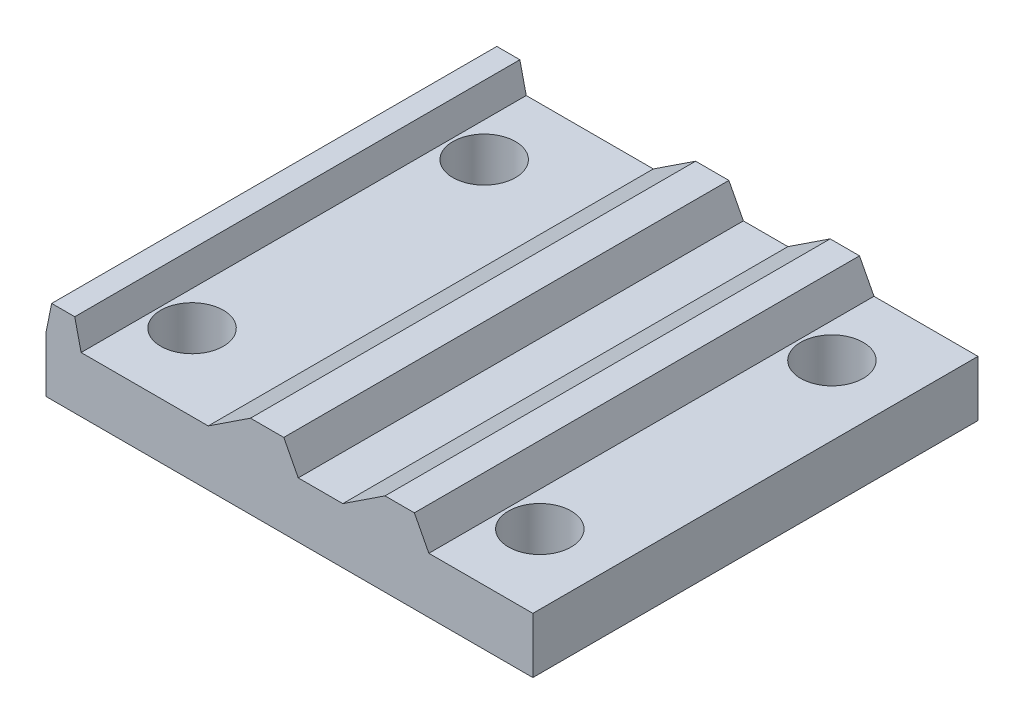
SolidWorks part; units mm, degrees
ref_plane "前视基准面" through (0, 0, 0) normal (0, 0, 1) x (1, 0, 0)
ref_plane "上视基准面" through (0, 0, 0) normal (0, 1, 0) x (1, 0, 0)
ref_plane "右视基准面" through (0, 0, 0) normal (1, 0, 0) x (0, 0, -1)
other "Configuration Table"
sketch "草图1" plane through (0, 0, 0) normal (0, 1, 0) x (1, 0, 0)
  line L0 (0, 0) -> (-4.3145, 0) construction
  line L1 (-17.5, -16) -> (17.5, -16)
  line L2 (-17.5, -16) -> (-17.5, 16)
  line L3 (-17.5, 16) -> (17.5, 16)
  line L4 (17.5, -16) -> (17.5, 16)
  line L5 (-17.5, -16) -> (17.5, 16) construction
  line L6 (-17.5, 16) -> (17.5, -16) construction
  line L7 (0, 0) -> (0, 5.4715) construction
  circle A0 centre (-12.5, 10.5) radius 2.25
  circle A1 centre (-12.5, -10.5) radius 2.25
  circle A2 centre (12.5, -10.5) radius 2.25
  circle A3 centre (12.5, 10.5) radius 2.25
  point P0 (0, 0)
  dimension "D3" = 4.5
  dimension "D1" = 35
  dimension "D2" = 32
  dimension "D4" = 21
  dimension "D5" = 25
extrude "凸台-拉伸1" add sketch "草图1" along normal blind 4
sketch "草图3" plane through (0, 0, 16) normal (0, 0, 1) x (1, 0, 0)
  line L0 (-17.5, 4) -> (-17.0918, 6)
  line L1 (-17.0918, 6) -> (-15.4333, 6)
  line L2 (-15.4333, 6) -> (-14.9752, 4)
  line L3 (-17.5, 4) -> (17.5, 4) construction
  line L4 (-14.9752, 4) -> (-10.8778, 4)
  line L8 (-8.0295, 4) -> (-5.8372, 4)
  line L9 (-5.8372, 4) -> (-2.8009, 6)
  line L10 (-2.8009, 6) -> (-0.4071, 6)
  line L11 (-0.4071, 6) -> (0.6341, 4)
  line L12 (0.6341, 4) -> (-5.8372, 4)
  line L13 (-8.0295, 4) -> (-10.8778, 4)
  line L14 (-14.9752, 4) -> (-17.5, 4)
  line L15 (3.8366, 4) -> (6.8729, 6)
  line L16 (6.8729, 6) -> (8.9819, 6)
  line L17 (8.9819, 6) -> (10.0231, 4)
  line L18 (-10.8778, 4) -> (-8.0295, 4)
  line L19 (-10.8778, 4) -> (-8.0295, 4)
  line M10 (17.5, 4) -> (-17.5, 4)
  dimension "D1" = 2
  dimension "D2" = 2
  dimension "D4" = 2
extrude "凸台-拉伸2" add sketch "草图3" against normal up to surface (32 mm away) contours L17 L16 L15 M10 | L11 L10 L9 M10 | L2 L1 L0 M10 up to face at (0, 2, -16)
